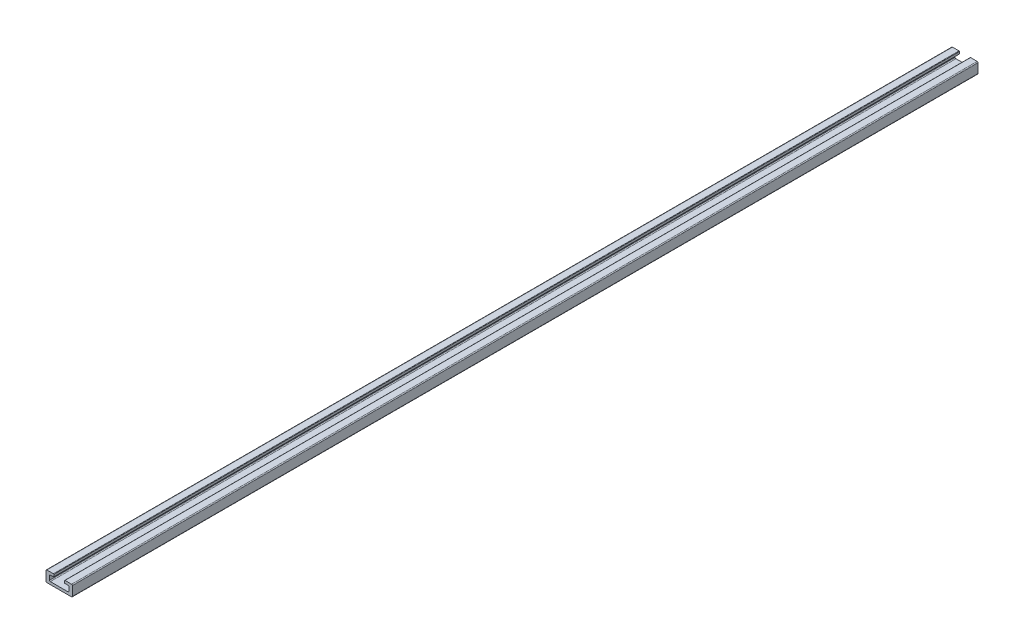
SolidWorks part; units mm, degrees
ref_plane "Front Plane" through (0, 0, 0) normal (0, 0, 1) x (1, 0, 0)
ref_plane "Top Plane" through (0, 0, 0) normal (0, 1, 0) x (1, 0, 0)
ref_plane "Right Plane" through (0, 0, 0) normal (1, 0, 0) x (0, 0, -1)
ref_plane "Plane1" through (0, 0, 0) normal (0, 0, 1) x (1, 0, 0)
sketch "Sketch1" plane through (0, 0, 0) normal (0, 0, 1) x (1, 0, 0)
  line L0 (-15, 5.25) -> (-15, -5.25)
  line L1 (-14, -6.25) -> (14, -6.25)
  line L2 (15, -5.25) -> (15, 5.25)
  line L3 (14, 6.25) -> (6.6, 6.25)
  line L4 (6.1, 5.75) -> (6.1, 3.45)
  line L5 (6.3, 3.25) -> (10, 3.25)
  line L6 (11, 2.25) -> (11, -2.25)
  line L7 (10, -3.25) -> (-10, -3.25)
  line L8 (-11, -2.25) -> (-11, 2.25)
  line L9 (-10, 3.25) -> (-6.3, 3.25)
  line L10 (-6.1, 3.45) -> (-6.1, 5.75)
  line L11 (-6.6, 6.25) -> (-14, 6.25)
  arc A0 (-15, -5.25) -> (-14, -6.25) centre (-14, -5.25) ccw
  arc A1 (14, -6.25) -> (15, -5.25) centre (14, -5.25) ccw
  arc A2 (15, 5.25) -> (14, 6.25) centre (14, 5.25) ccw
  arc A3 (6.6, 6.25) -> (6.1, 5.75) centre (6.6, 5.75) ccw
  arc A4 (6.1, 3.45) -> (6.3, 3.25) centre (6.3, 3.45) ccw
  arc A5 (10, 3.25) -> (11, 2.25) centre (10, 2.25) cw
  arc A6 (11, -2.25) -> (10, -3.25) centre (10, -2.25) cw
  arc A7 (-10, -3.25) -> (-11, -2.25) centre (-10, -2.25) cw
  arc A8 (-11, 2.25) -> (-10, 3.25) centre (-10, 2.25) cw
  arc A9 (-6.3, 3.25) -> (-6.1, 3.45) centre (-6.3, 3.45) ccw
  arc A10 (-6.1, 5.75) -> (-6.6, 6.25) centre (-6.6, 5.75) ccw
  arc A11 (-14, 6.25) -> (-15, 5.25) centre (-14, 5.25) ccw
extrude "Boss-Extrude1" add sketch "Sketch1" against normal blind 995 and the other way blind 35
ref_plane "Plane2" through (0, 0, 0) normal (1, 0, 0) x (0, 0, -1)
sketch "Sketch2" plane through (0, 0, 0) normal (1, 0, 0) x (0, 0, -1)
  line L0 (-20, -3.25) -> (-17, -3.25)
  line L1 (-17, -3.25) -> (-17, -5.25)
  line L2 (-17, -5.25) -> (-18.25, -5.25)
  line L3 (-18.25, -5.25) -> (-18.25, -6.25)
  line L4 (-18.25, -6.25) -> (-20, -6.25)
  line L5 (-20, -6.25) -> (-20, -3.25)
  line L6 (-20, -6.25) -> (-20, -3.25) construction
revolve "Cut-Revolve1" cut sketch "Sketch2" angle 360 about L6
ref_plane "Plane3" through (0, 0, 0) normal (1, 0, 0) x (0, 0, -1)
sketch "Sketch3" plane through (0, 0, 0) normal (1, 0, 0) x (0, 0, -1)
  line L0 (20, -3.25) -> (23, -3.25)
  line L1 (23, -3.25) -> (23, -5.25)
  line L2 (23, -5.25) -> (21.75, -5.25)
  line L3 (21.75, -5.25) -> (21.75, -6.25)
  line L4 (21.75, -6.25) -> (20, -6.25)
  line L5 (20, -6.25) -> (20, -3.25)
  line L6 (20, -6.25) -> (20, -3.25) construction
revolve "Cut-Revolve2" cut sketch "Sketch3" angle 360 about L6
pattern_linear "LPattern1" count 25 spacing 40 along (0, 0, -1) of "Cut-Revolve2"
